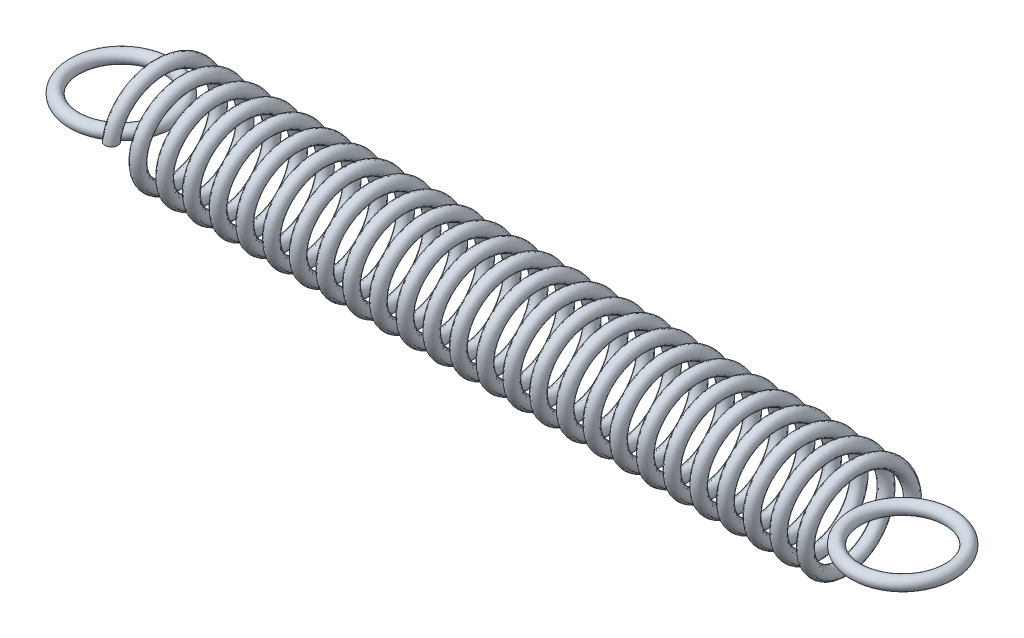
SolidWorks part; units mm, degrees
ref_plane "Front Plane" through (0, 0, 0) normal (0, 0, 1) x (1, 0, 0)
ref_plane "Top Plane" through (0, 0, 0) normal (0, 1, 0) x (1, 0, 0)
ref_plane "Right Plane" through (0, 0, 0) normal (1, 0, 0) x (0, 0, -1)
sketch "Sketch1" plane through (0, 0, 0) normal (1, 0, 0) x (0, 0, -1)
  circle A0 centre (0, 0) radius 4.4577
  dimension "D1" = 8.9154
sketch "Sketch3" plane through (0, 0, 0) normal (0, 0, 1) x (1, 0, 0)
  line L0 (0, -4.4577) -> (0, 4.4577) construction
  circle A0 centre (0, 4.4577) radius 0.6096
  dimension "D1" = 1.2192
curve "Helix/Spiral1" pitch 2.54 height 67.31 turns 26.5
sweep "Sweep1" add profiles "Sketch3" path "Helix/Spiral1"
sketch "Sketch4" plane through (0, 0, 0) normal (0, -1, 0) x (1, 0, 0)
  circle A0 centre (-4.1501, 0) radius 5.0673
  circle A1 centre (-0.635, 4.4577) radius 0.6096 construction
  dimension "D2" = 10.1346
ref_plane "Plane1" through (-4.1501, 0, 0) normal (1, 0, 0) x (0, 0, -1)
sketch "Sketch5" plane through (-4.1501, 0, 0) normal (1, 0, 0) x (0, 0, -1)
  circle A0 centre (4.4577, 0) radius 0.6096
  dimension "D2" = 1.2192
  dimension "D1" = 4.4577
sweep "Sweep2" add profiles "Sketch5" path "Sketch4"
sketch "Sketch6" plane through (0, 0, 0) normal (0, -1, 0) x (1, 0, 0)
  circle A0 centre (70.1901, 0) radius 5.0673
  circle A2 centre (66.675, -4.4577) radius 0.6096 construction
  dimension "D1" = 10.1346
ref_plane "Plane2" through (70.1901, 0, 0) normal (1, 0, 0) x (0, 0, -1)
sketch "Sketch7" plane through (70.1901, 0, 0) normal (1, 0, 0) x (0, 0, -1)
  circle A0 centre (-4.4577, 0) radius 0.6096
  dimension "D2" = 1.2192
  dimension "D1" = 4.4577
sweep "Sweep3" add profiles "Sketch7" path "Sketch6"
